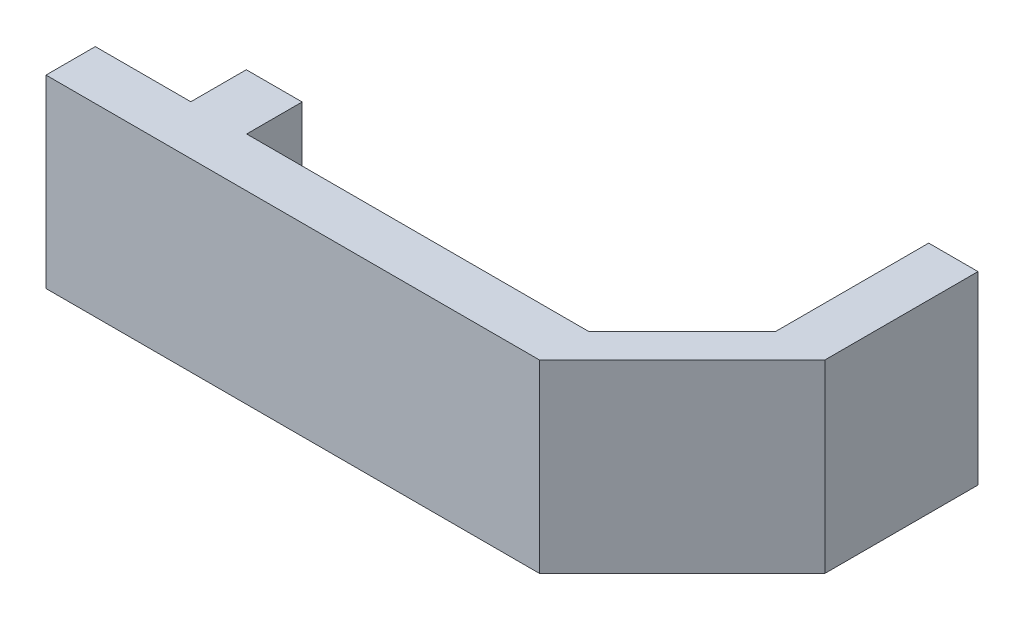
SolidWorks part; units mm, degrees
ref_plane "前基準面" through (0, 0, 0) normal (0, 0, 1) x (1, 0, 0)
ref_plane "上基準面" through (0, 0, 0) normal (0, 1, 0) x (1, 0, 0)
ref_plane "右基準面" through (0, 0, 0) normal (1, 0, 0) x (0, 0, -1)
sketch "草圖1" plane through (0, 0, 0) normal (0, 1, 0) x (1, 0, 0)
  line L0 (-27.5017, 6.8593) -> (-22.9717, 6.8593)
  line L1 (-22.9717, 6.8593) -> (-22.9717, 2.3593)
  line L2 (-22.9717, 2.3593) -> (4.7783, 2.3593)
  line L3 (4.7783, 2.3593) -> (12.3616, 9.9426)
  line L4 (12.3616, 9.9426) -> (12.3616, 22.3593)
  line L5 (-27.5017, 6.8593) -> (-27.5017, 2.3593)
  line L6 (-27.5017, 2.3593) -> (-35.2517, 2.3593)
  line L7 (-35.2517, 2.3593) -> (-35.2517, -1.6407)
  line L8 (-35.2517, -1.6407) -> (4.7783, -1.6407)
  line L12 (4.7783, -1.6407) -> (16.3616, 9.9426)
  line L13 (12.3616, 22.3593) -> (16.3616, 22.3593)
  line L14 (16.3616, 22.3593) -> (16.3616, 9.9426)
  dimension "D1" = 4.53
  dimension "D2" = 4.5
  dimension "D3" = 4
  dimension "D4" = 4
  dimension "D5" = 7.75
  dimension "D6" = 27.75
  dimension "D7" = 20
extrude "填料-伸長1" add sketch "草圖1" along normal blind 15
